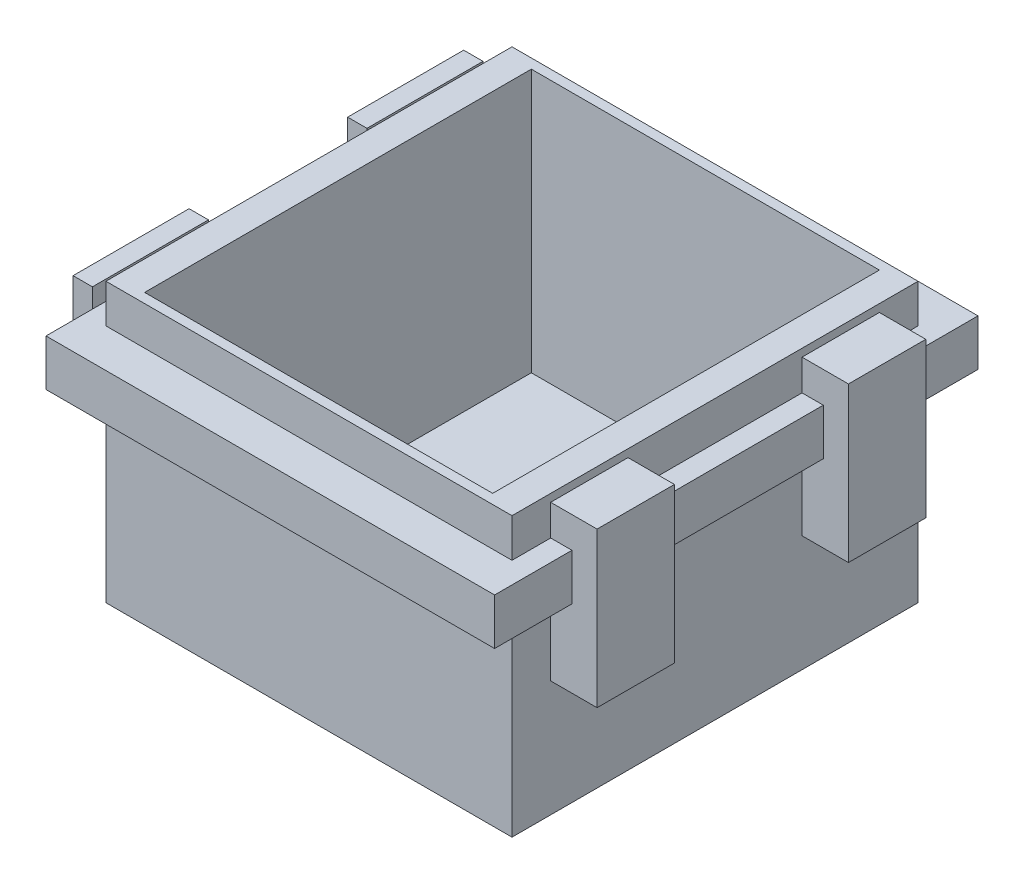
SolidWorks part; units mm, degrees
ref_plane "Front Plane" through (0, 0, 0) normal (0, 0, 1) x (1, 0, 0)
ref_plane "Top Plane" through (0, 0, 0) normal (0, 1, 0) x (1, 0, 0)
ref_plane "Right Plane" through (0, 0, 0) normal (1, 0, 0) x (0, 0, -1)
other "Configuration Table"
sketch "Sketch1" plane through (0, 0, 0) normal (0, 1, 0) x (1, 0, 0)
  line L5 (-66.675, -66.675) -> (66.675, -66.675)
  line L6 (-66.675, -66.675) -> (-66.675, 66.675)
  line L7 (-66.675, 66.675) -> (66.675, 66.675)
  line L8 (66.675, -66.675) -> (66.675, 66.675)
  line L9 (-66.675, -66.675) -> (66.675, 66.675) construction
  line L10 (-66.675, 66.675) -> (66.675, -66.675) construction
  point P0 (0, 0)
  dimension "D1" = 133.35
  dimension "D2" = 133.35
extrude "Boss-Extrude1" add sketch "Sketch1" along normal blind 63.5
sketch "Sketch2" plane through (0, 63.5, 0) normal (0, 1, 0) x (1, 0, 0)
  line L1 (-73.66, -79.375) -> (73.66, -79.375)
  line L2 (-73.66, -79.375) -> (-73.66, 79.375)
  line L3 (-73.66, 79.375) -> (73.66, 79.375)
  line L4 (73.66, -79.375) -> (73.66, 79.375)
  line L5 (-73.66, -79.375) -> (73.66, 79.375) construction
  line L6 (-73.66, 79.375) -> (73.66, -79.375) construction
  point P0 (0, 0)
  dimension "D1" = 158.75
  dimension "D2" = 147.32
extrude "Boss-Extrude2" add sketch "Sketch2" along normal blind 15.24
sketch "Sketch3" plane through (0, 78.74, 0) normal (0, 1, 0) x (1, 0, 0)
  line L1 (-66.675, 66.675) -> (66.675, 66.675)
  line L2 (-66.675, 66.675) -> (-66.675, -66.675)
  line L3 (-66.675, -66.675) -> (66.675, -66.675)
  line L4 (66.675, 66.675) -> (66.675, -66.675)
  line L5 (-66.675, 66.675) -> (66.675, -66.675) construction
  line L6 (-66.675, -66.675) -> (66.675, 66.675) construction
  point P0 (0, 0)
  dimension "D1" = 133.35
  dimension "D2" = 133.35
extrude "Boss-Extrude3" add sketch "Sketch3" along normal blind 12.7
sketch "Sketch4" plane through (-73.66, 0, 0) normal (-1, 0, 0) x (0, 0, 1)
  line L0 (79.375, 78.74) -> (79.375, 63.5) construction
  line L1 (26.035, 85.09) -> (64.135, 85.09)
  line L2 (26.035, 85.09) -> (26.035, 66.04)
  line L3 (26.035, 66.04) -> (64.135, 66.04)
  line L4 (64.135, 85.09) -> (64.135, 66.04)
  line L5 (-66.675, 91.44) -> (66.675, 91.44) construction
  dimension "D1" = 38.1
  dimension "D2" = 19.05
  dimension "D3" = 15.24
  dimension "D4" = 6.35
extrude "Boss-Extrude4" add sketch "Sketch4" along normal blind 6.35
mirror "Mirror1" about plane through (0, 0, 0) normal (0, 0, 1) of "Boss-Extrude4"
sketch "Sketch5" plane through (66.675, 0, 0) normal (1, 0, 0) x (0, 0, -1)
  line L0 (-66.675, 0) -> (66.675, 0) construction
  line L1 (-53.975, 38.1) -> (-28.575, 38.1)
  line L2 (-53.975, 38.1) -> (-53.975, 88.9)
  line L3 (-53.975, 88.9) -> (-28.575, 88.9)
  line L4 (-28.575, 38.1) -> (-28.575, 88.9)
  line L5 (-66.675, 63.5) -> (-66.675, 0) construction
  dimension "D1" = 25.4
  dimension "D2" = 50.8
  dimension "D3" = 38.1
  dimension "D4" = 12.7
extrude "Boss-Extrude5" add sketch "Sketch5" along normal blind 15.24
mirror "Mirror2" about plane through (0, 0, 0) normal (0, 0, 1) of "Boss-Extrude5"
sketch "Sketch7" plane through (0, 91.44, 0) normal (0, 1, 0) x (1, 0, 0)
  line L1 (-57.15, -63.5) -> (57.15, -63.5)
  line L2 (-57.15, -63.5) -> (-57.15, 63.5)
  line L3 (-57.15, 63.5) -> (57.15, 63.5)
  line L4 (57.15, -63.5) -> (57.15, 63.5)
  line L5 (-57.15, -63.5) -> (57.15, 63.5) construction
  line L6 (-57.15, 63.5) -> (57.15, -63.5) construction
  point P0 (0, 0)
  dimension "D1" = 127
  dimension "D2" = 114.3
extrude "Cut-Extrude1" cut sketch "Sketch7" against normal blind 86.36
